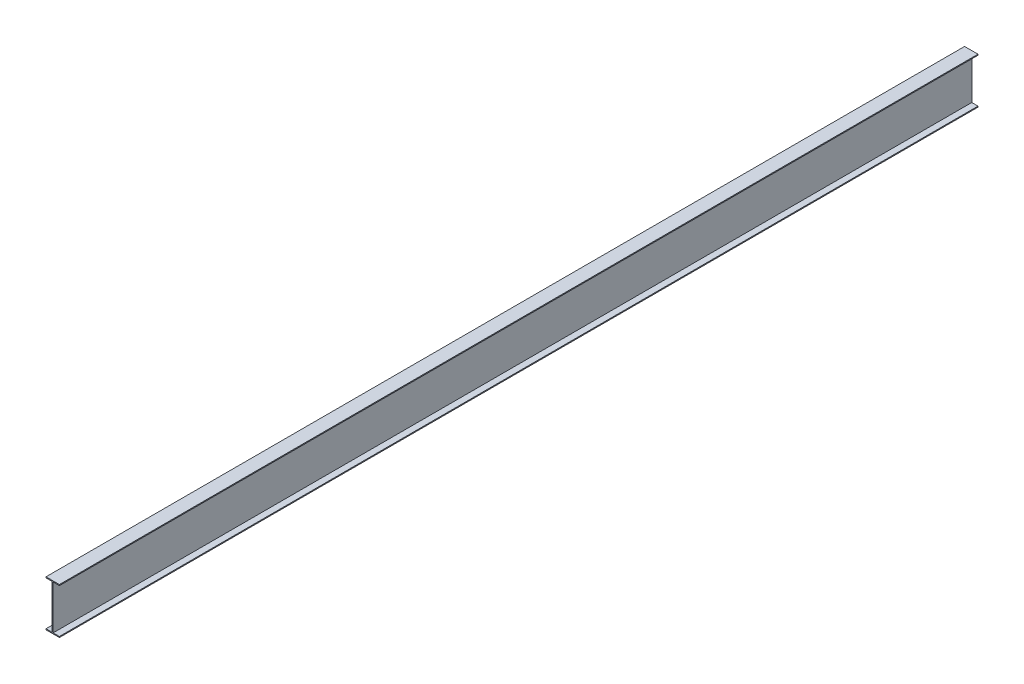
SolidWorks part; units mm, degrees
ref_plane "Front" through (0, 0, 0) normal (0, 0, 1) x (1, 0, 0)
ref_plane "Top" through (0, 0, 0) normal (0, 1, 0) x (1, 0, 0)
ref_plane "Right" through (0, 0, 0) normal (1, 0, 0) x (0, 0, -1)
sketch "Sketch1" plane through (0, 0, 0) normal (0, 0, 1) x (1, 0, 0)
  line L0 (0, -292.1) -> (0, 292.1) construction
  line L1 (-6.35, 292.1) -> (6.35, 292.1) construction
  line L2 (-6.35, 292.1) -> (-6.35, -292.1)
  line L3 (-6.35, -292.1) -> (6.35, -292.1) construction
  line L4 (6.35, 292.1) -> (6.35, -292.1)
  line L5 (-6.35, 292.1) -> (6.35, -292.1) construction
  line L6 (-6.35, -292.1) -> (6.35, 292.1) construction
  line L7 (-6.35, 292.1) -> (-88.9, 292.1)
  line L8 (-88.9, 292.1) -> (-88.9, 304.8)
  line L9 (-88.9, 304.8) -> (88.9, 304.8)
  line L10 (88.9, 304.8) -> (88.9, 292.1)
  line L11 (88.9, 292.1) -> (6.35, 292.1)
  line L12 (6.35, -292.1) -> (88.9, -292.1)
  line L13 (88.9, -292.1) -> (88.9, -304.8)
  line L14 (88.9, -304.8) -> (-88.9, -304.8)
  line L15 (-88.9, -304.8) -> (-88.9, -292.1)
  line L16 (-88.9, -292.1) -> (-6.35, -292.1)
  point P0 (0, 0)
  dimension "D1" = 12.7
  dimension "D2" = 584.2
  dimension "D3" = 177.8
extrude "Boss-Extrude1" add sketch "Sketch1" along normal blind 12192
